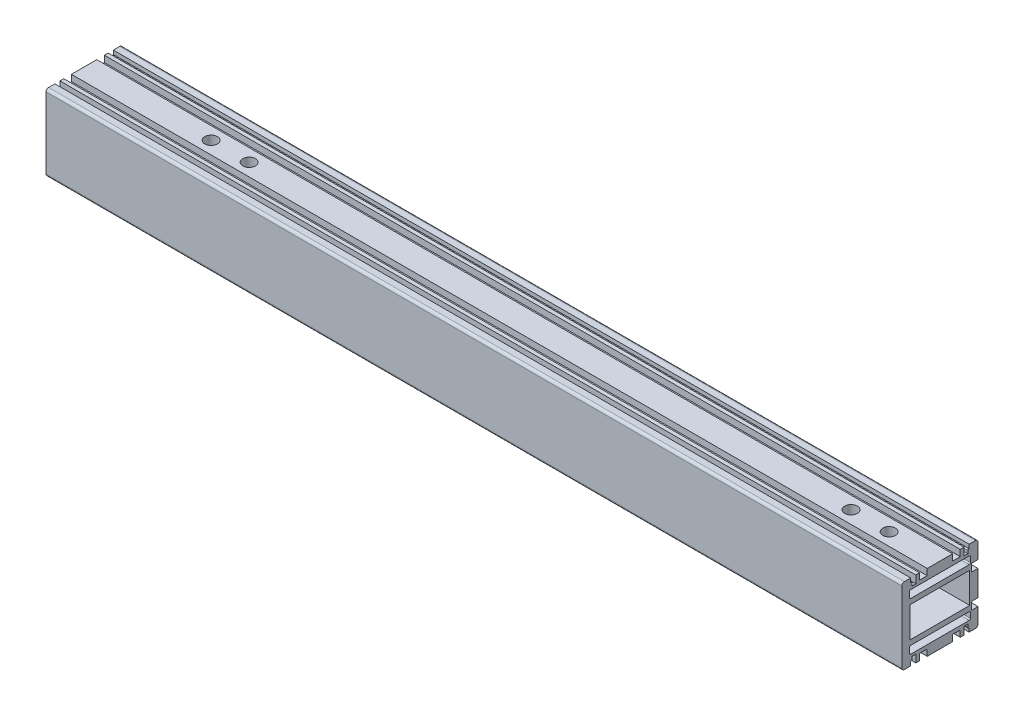
SolidWorks part; units mm, degrees
ref_plane "前视基准面" through (0, 0, 0) normal (0, 0, 1) x (1, 0, 0)
ref_plane "上视基准面" through (0, 0, 0) normal (0, 1, 0) x (1, 0, 0)
ref_plane "右视基准面" through (0, 0, 0) normal (1, 0, 0) x (0, 0, -1)
sketch "草图1" plane through (0, 0, 0) normal (1, 0, 0) x (0, 0, -1)
  line L0 (-15, 15) -> (15, -15) construction
  line L1 (-14, 15) -> (-11.5, 15)
  line L2 (-15, 14) -> (-15, -14)
  line L3 (-14, -15) -> (-11.5, -15)
  line L4 (15, 14) -> (15, 8)
  line L5 (15, 15) -> (-15, -15) construction
  line L6 (-11.5, 15) -> (-11.5, 13.5)
  line L7 (-11.5, 13.5) -> (-11.4, 13.5)
  line L8 (-11, 13.1) -> (-11, 12)
  line L9 (-11, 12) -> (-9.5, 12)
  line L10 (-9.5, 12) -> (-9.5, 15)
  line L11 (-9.5, 15) -> (-8, 15)
  line L12 (-8, 15) -> (-8, 12.5)
  line L13 (-8, 12.5) -> (-5, 12.5)
  line L14 (-5, 12.5) -> (-5, 15)
  line L15 (-5, 15) -> (5, 15)
  line L16 (0, 21.5201) -> (0, -18.309) construction
  line L17 (0, 55) -> (0, -55) construction
  line L18 (5, 12.5) -> (5, 15)
  line L19 (8, 12.5) -> (5, 12.5)
  line L20 (8, 15) -> (8, 12.5)
  line L21 (9.5, 15) -> (8, 15)
  line L22 (9.5, 12) -> (9.5, 15)
  line L23 (11, 12) -> (9.5, 12)
  line L24 (11, 13.1) -> (11, 12)
  line L25 (11.5, 13.5) -> (11.4, 13.5)
  line L26 (11.5, 15) -> (11.5, 13.5)
  line L27 (8, 15) -> (9.5, 15)
  line L28 (11.5, 15) -> (14, 15)
  line L29 (-19.8303, 0) -> (22.13, 0) construction
  line L30 (55, 0) -> (-55, 0) construction
  line L31 (8, -15) -> (9.5, -15)
  line L32 (11.5, -15) -> (11.5, -13.5)
  line L33 (11.5, -13.5) -> (11.4, -13.5)
  line L34 (11, -13.1) -> (11, -12)
  line L35 (11, -12) -> (9.5, -12)
  line L36 (9.5, -12) -> (9.5, -15)
  line L37 (9.5, -15) -> (8, -15)
  line L38 (8, -15) -> (8, -12.5)
  line L39 (8, -12.5) -> (5, -12.5)
  line L40 (5, -12.5) -> (5, -15)
  line L41 (-5, -15) -> (5, -15)
  line L42 (-5, -12.5) -> (-5, -15)
  line L43 (-8, -12.5) -> (-5, -12.5)
  line L44 (-8, -15) -> (-8, -12.5)
  line L45 (-9.5, -15) -> (-8, -15)
  line L46 (-9.5, -12) -> (-9.5, -15)
  line L47 (-11, -12) -> (-9.5, -12)
  line L48 (-11, -13.1) -> (-11, -12)
  line L49 (-11.5, -13.5) -> (-11.4, -13.5)
  line L50 (-11.5, -15) -> (-11.5, -13.5)
  line L51 (-9.5, -15) -> (-8, -15)
  line L52 (-5, -15) -> (5, -15)
  line L53 (8, -15) -> (9.5, -15)
  line L54 (11.5, -15) -> (14, -15)
  line L55 (15, 8) -> (12.5, 8)
  line L56 (12.5, 8) -> (12.5, 5)
  line L57 (12.5, 5) -> (15, 5)
  line L58 (12.5, -5) -> (15, -5)
  line L59 (12.5, -8) -> (12.5, -5)
  line L60 (15, -8) -> (12.5, -8)
  line L61 (15, 5) -> (15, -5)
  line L62 (15, -8) -> (15, -14)
  line L63 (12, -10.5) -> (12, -8.5)
  line L64 (-11.5, 11) -> (11.5, 11)
  line L65 (-12, 10.5) -> (-12, 8.5)
  line L66 (-11.5, 8) -> (11.5, 8)
  line L67 (12, 10.5) -> (12, 8.5)
  line L68 (-11.5, -8) -> (11.5, -8)
  line L69 (-12, -10.5) -> (-12, -8.5)
  line L70 (-11.5, -11) -> (11.5, -11)
  line L72 (-11.75, 6) -> (11.75, 6)
  line L73 (-11.75, 6) -> (-11.75, -6)
  line L74 (-11.75, -6) -> (11.75, -6)
  line L75 (11.75, 6) -> (11.75, -6)
  arc A0 (12, 8.5) -> (11.5, 8) centre (11.5, 8.5) cw
  arc A1 (11.5, 11) -> (12, 10.5) centre (11.5, 10.5) cw
  arc A2 (-11.5, 11) -> (-12, 10.5) centre (-11.5, 10.5) ccw
  arc A3 (-11.5, 8) -> (-12, 8.5) centre (-11.5, 8.5) cw
  arc A4 (-11, -13.1) -> (-11.4, -13.5) centre (-11.4, -13.1) cw
  arc A5 (11.4, -13.5) -> (11, -13.1) centre (11.4, -13.1) cw
  arc A6 (11.4, 13.5) -> (11, 13.1) centre (11.4, 13.1) ccw
  arc A7 (-11, 13.1) -> (-11.4, 13.5) centre (-11.4, 13.1) ccw
  arc A8 (-11.5, -8) -> (-12, -8.5) centre (-11.5, -8.5) ccw
  arc A9 (-11.5, -11) -> (-12, -10.5) centre (-11.5, -10.5) cw
  arc A10 (11.5, -11) -> (12, -10.5) centre (11.5, -10.5) ccw
  arc A11 (12, -8.5) -> (11.5, -8) centre (11.5, -8.5) ccw
  arc A12 (14, 15) -> (15, 14) centre (14, 14) cw
  arc A13 (14, -15) -> (15, -14) centre (14, -14) ccw
  arc A14 (-15, -14) -> (-14, -15) centre (-14, -14) ccw
  arc A15 (-15, 14) -> (-14, 15) centre (-14, 14) cw
  point P69 (12, 11)
  point P72 (-12, 11)
  point P77 (-11, -13.5)
  point P80 (11, -13.5)
  point P83 (11, 13.5)
  point P86 (-11, 13.5)
  point P99 (-12, -11)
  point P100 (12, -11)
  dimension "D17" = 0.5
  dimension "D18" = 0.4
  dimension "D21" = 1
  dimension "D1" = 3.5
  dimension "D2" = 1.5
  dimension "D3" = 0.5
  dimension "D4" = 1.5
  dimension "D5" = 3
  dimension "D6" = 30
  dimension "D7" = 30
  dimension "D8" = 1.5
  dimension "D9" = 2.5
  dimension "D10" = 3
  dimension "D11" = 2.5
  dimension "D12" = 7
  dimension "D13" = 3
  dimension "D14" = 4
  dimension "D15" = 3
  dimension "D16" = 24
  dimension "D19" = 23.5
  dimension "D20" = 12
extrude "凸台-拉伸1" add sketch "草图1" along normal mid plane 337 contours A15 L2 A14 L3 L50 L49 A4 L48 L47 L46 L45 L44 L43 L42 L41 L40 L39 L38 L31 L36 L35 L34 A5 L33 L32 L54 A13 L62 L60 L59 L58 L61 L57 L56 L55 L4 A12 L28 L26 L25 A6 L24 L23 L22 L21 L20 L19 L18 L15 L14 L13
hole_wizard "M6 螺纹孔1" positions "草图3" profile "草图2" tap size "M6" standard "GB"
sketch "草图3" plane through (0, 15, 0) normal (0, 1, 0) x (-1, 0, 0)
  line L0 (-168.5, 5) -> (-168.5, -5) construction
  line L1 (-168.5, 15) -> (168.5, 15) construction
  point P0 (-148.5, 0)
  point P1 (-133.5, 0)
  point P4 (103.5, 0)
  point P7 (118.5, 0)
  dimension "D1" = 20
  dimension "D2" = 15
sketch "草图2" plane through (148.5, 15, 0) normal (1, 0, 0) x (0, 0, 1)
  line L0 (0, 0) -> (0, 16.5022)
  line L1 (0, 16.5022) -> (2.5, 15)
  line L2 (2.5, 15) -> (2.5, 0)
  line L5 (2.5, 0) -> (0, 0)
  line L10 (0, 16.5022) -> (-2.5, 15) construction
  line L11 (0, -6.35) -> (0, 107.95) construction
  dimension "螺纹孔钻头直径" = 5
  dimension "螺纹孔钻头深度" = 15
  dimension "导头角度" = 118
cosmetic thread "孔螺蚊线1" parameters "D1"=9, "D2"=6
cosmetic thread "孔螺蚊线2" parameters "D1"=9, "D2"=6
cosmetic thread "孔螺蚊线3" parameters "D1"=9, "D2"=6
cosmetic thread "孔螺蚊线4" parameters "D1"=9, "D2"=6
